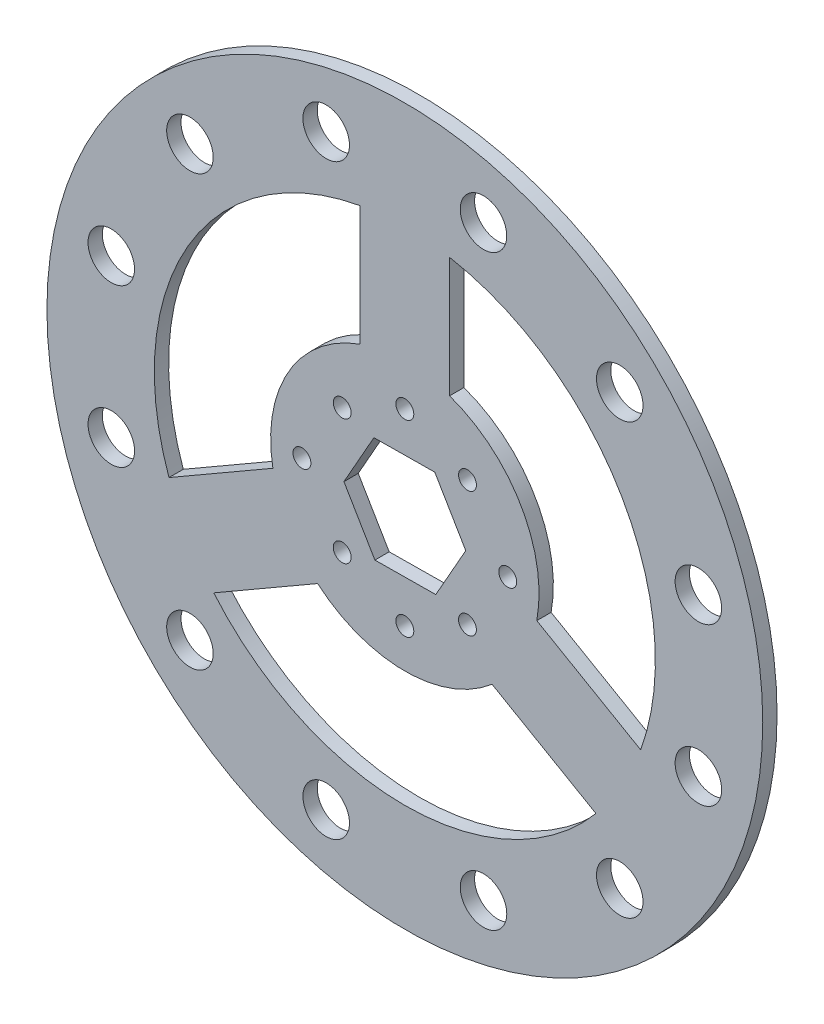
SolidWorks part; units mm, degrees
ref_plane "前视基准面" through (0, 0, 0) normal (0, 0, 1) x (1, 0, 0)
ref_plane "上视基准面" through (0, 0, 0) normal (0, 1, 0) x (1, 0, 0)
ref_plane "右视基准面" through (0, 0, 0) normal (1, 0, 0) x (0, 0, -1)
other "Configuration Table"
sketch "草图8" plane through (0, 0, 0) normal (0, 0, 1) x (1, 0, 0)
  line L0 (-58.7366, 24.6775) -> (-58.7366, 11.2697)
  line L1 (-57.0852, -8.7995) -> (-50.278, -8.736)
  line L2 (-50.278, -8.736) -> (-46.9293, -2.809)
  line L3 (-46.9293, -2.809) -> (-50.3879, 3.0545)
  line L4 (-50.3879, 3.0545) -> (-57.1952, 2.991)
  line L5 (-57.1952, 2.991) -> (-60.5438, -2.936)
  line L6 (-60.5438, -2.936) -> (-57.0852, -8.7995)
  line L7 (-48.7366, 24.6775) -> (-48.7366, 11.2697)
  line L8 (-27.3776, -12.3173) -> (-38.9891, -5.6134)
  line L9 (-32.3776, -20.9776) -> (-43.9891, -14.2737)
  line L10 (-75.0955, -20.9776) -> (-63.484, -14.2737)
  line L11 (-80.0955, -12.3173) -> (-68.484, -5.6134)
  circle A0 centre (-53.7366, -2.8725) radius 40
  arc A1 (-58.7366, 24.6775) -> (-80.0955, -12.3173) centre (-53.7366, -2.8725) ccw
  arc A2 (-58.7366, 11.2697) -> (-68.484, -5.6134) centre (-53.7366, -2.8725) ccw
  circle A3 centre (-53.7366, 7.5004) radius 1
  circle A4 centre (-46.7352, 4.1278) radius 1
  circle A5 centre (-42.2364, -2.9995) radius 1
  circle A6 centre (-46.7378, -9.8697) radius 1
  circle A7 centre (-53.7366, -13.4996) radius 1
  circle A8 centre (-60.7376, -9.8723) radius 1
  circle A9 centre (-65.2364, -2.9995) radius 1
  circle A10 centre (-60.7358, 4.1281) radius 1
  circle A11 centre (-62.5281, 29.9344) radius 2.6
  circle A12 centre (-44.9468, 29.9349) radius 2.6
  circle A13 centre (-29.7207, 21.1446) radius 2.6
  circle A14 centre (-20.9297, 5.919) radius 2.6
  circle A15 centre (-20.9292, -11.6623) radius 2.6
  circle A16 centre (-29.7195, -26.8883) radius 2.6
  circle A17 centre (-44.9451, -35.6794) radius 2.6
  circle A18 centre (-62.5263, -35.6798) radius 2.6
  circle A19 centre (-77.7524, -26.8896) radius 2.6
  circle A20 centre (-86.5435, -11.664) radius 2.6
  circle A21 centre (-86.5439, 5.9173) radius 2.6
  circle A22 centre (-77.7537, 21.1434) radius 2.6
  circle A23 centre (-53.7366, -2.8725) radius 6.8075 construction
  arc A24 (-75.0955, -20.9776) -> (-32.3776, -20.9776) centre (-53.7366, -2.8725) ccw
  arc A25 (-63.484, -14.2737) -> (-43.9891, -14.2737) centre (-53.7366, -2.8725) ccw
  arc A26 (-38.9891, -5.6134) -> (-48.7366, 11.2697) centre (-53.7366, -2.8725) ccw
  arc A27 (-27.3776, -12.3173) -> (-48.7366, 24.6775) centre (-53.7366, -2.8725) ccw
  point P57 (-53.7366, -2.8725)
  point P79 (-53.7366, -2.8725)
extrude "凸台-拉伸3" add sketch "草图8" along normal blind 1.6
